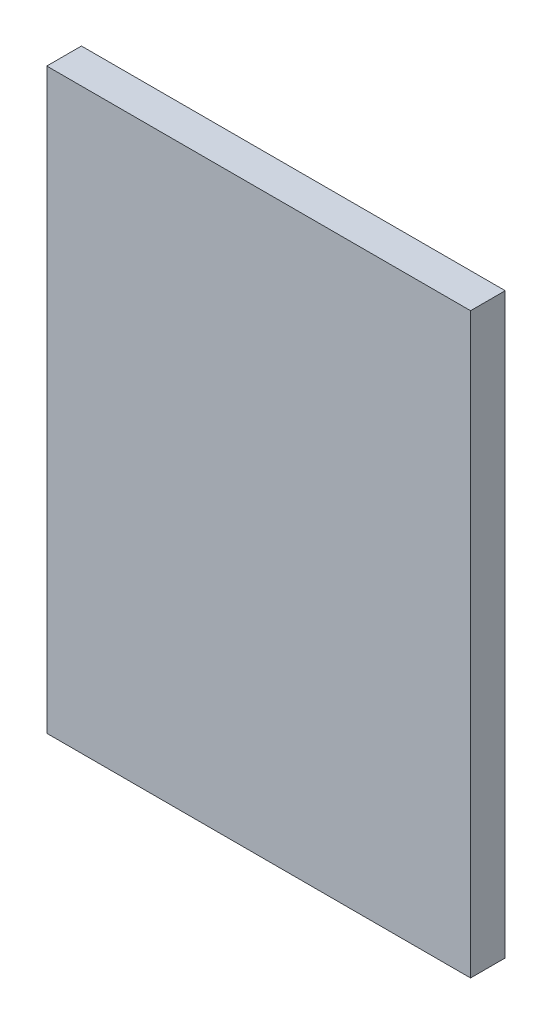
SolidWorks part; units mm, degrees
ref_plane "Front Plane" through (0, 0, 0) normal (0, 0, 1) x (1, 0, 0)
ref_plane "Top Plane" through (0, 0, 0) normal (0, 1, 0) x (1, 0, 0)
ref_plane "Right Plane" through (0, 0, 0) normal (1, 0, 0) x (0, 0, -1)
sketch "Sketch1" plane through (0, 0, 0) normal (0, 0, 1) x (1, 0, 0)
  line L1 (-110, -150) -> (110, -150)
  line L2 (-110, -150) -> (-110, 150)
  line L3 (-110, 150) -> (110, 150)
  line L4 (110, -150) -> (110, 150)
  line L5 (-110, -150) -> (110, 150) construction
  line L6 (-110, 150) -> (110, -150) construction
  point P0 (0, 0)
  dimension "D1" = 220
  dimension "D2" = 300
extrude "Boss-Extrude1" add sketch "Sketch1" along normal blind 18
